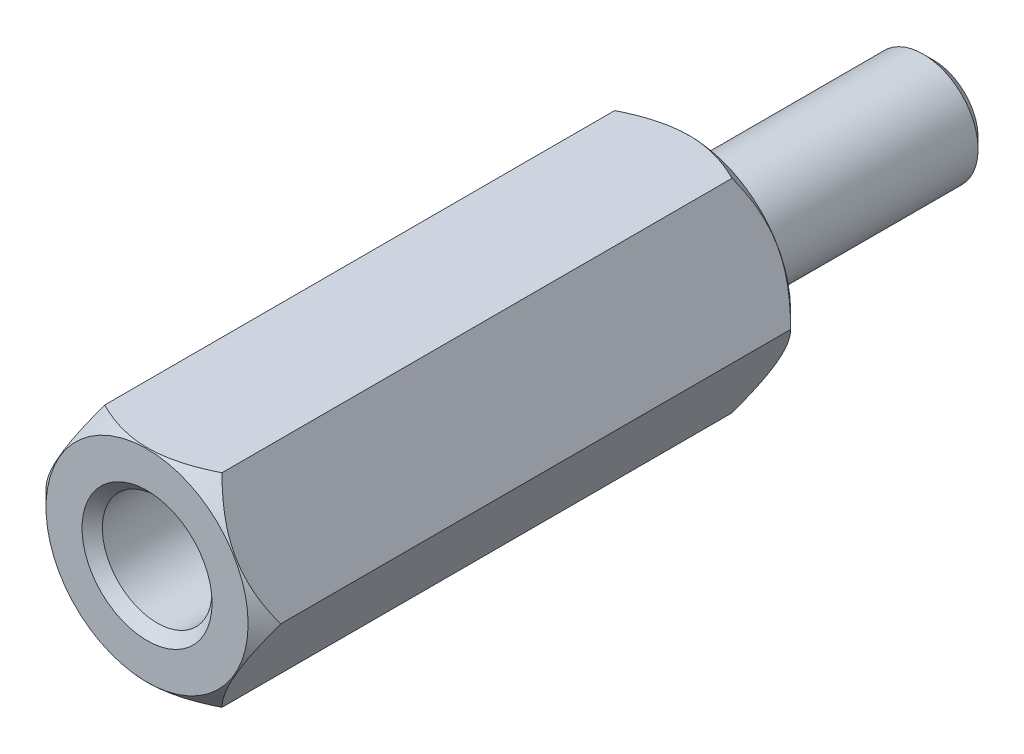
SolidWorks part; units mm, degrees
material "Brass"
ref_plane "Front Plane" through (0, 0, 0) normal (0, 0, 1) x (1, 0, 0)
ref_plane "Top Plane" through (0, 0, 0) normal (0, 1, 0) x (1, 0, 0)
ref_plane "Right Plane" through (0, 0, 0) normal (1, 0, 0) x (0, 0, -1)
ref_axis "Axis1" through (0, 0, 15.2667) along (0, 0, -1)
sketch "Sketch1" plane through (0, 0, 0) normal (0, 0, 1) x (1, 0, 0)
  line L1 (2.8868, 0) -> (1.4434, 2.5)
  line L2 (1.4434, 2.5) -> (-1.4434, 2.5)
  line L3 (-1.4434, 2.5) -> (-2.8868, 0)
  line L4 (-2.8868, 0) -> (-1.4434, -2.5)
  line L5 (-1.4434, -2.5) -> (1.4434, -2.5)
  line L6 (1.4434, -2.5) -> (2.8868, 0)
  circle A0 centre (0, 0) radius 2.5 construction
  dimension "D1" = 5
extrude "HEX" add sketch "Sketch1" along normal mid plane 13.35
hole_wizard "Tap Drill for M3x0.5 Tap1" positions "Sketch5" profile "Sketch6" hole size "M3x0.5" standard "BSI" end condition through all
sketch "Sketch5" plane through (0, 0, 6.675) normal (0, 0, 1) x (1, 0, 0)
  point P0 (0, 0)
sketch "Sketch6" plane through (0, 0, 6.675) normal (1, 0, 0) x (0, -1, 0)
  line L0 (0, 0) -> (0, 13.35)
  line L1 (0, 13.35) -> (1.35, 13.35)
  line L2 (1.35, 13.35) -> (1.35, 0)
  line L5 (1.35, 0) -> (0, 0)
  line L11 (0, -6.35) -> (0, 107.95) construction
  dimension "Thru Hole Dia." = 2.7
  dimension "Thru Hole Depth" = 13.35
sketch "Sketch7" plane through (0, 0, 0) normal (0, 1, 0) x (1, 0, 0)
  line L0 (-2.8868, 6.675) -> (-2.8868, 6.275)
  line L1 (-2.8868, -6.675) -> (-2.8868, 6.675) construction
  line L2 (-2.8868, 6.675) -> (-2.4868, 6.675)
  line L3 (-1.4434, 6.675) -> (-2.8868, 6.675) construction
  line L4 (-2.4868, 6.675) -> (-2.8868, 6.275)
  dimension "D1" = 0.4
revolve "HexChamfer" cut sketch "Sketch7" angle 360 about axis through (0, 0, 15.2667) along (0, 0, -1)
mirror "Mirror1" about plane through (0, 0, 0) normal (0, 0, 1) of "HexChamfer"
sketch "Sketch8" plane through (0, 0, -6.675) normal (0, 0, -1) x (-1, 0, 0)
  circle A0 centre (0, 0) radius 1.35
  dimension "D1" = 2.7
extrude "Thread" add sketch "Sketch8" along normal blind 6 and the other way blind 2
chamfer "InnerChamfer" distance 0.25 angle 45 3 edges at (1.35, 0, 6.675) (-1.35, 0, -12.675) (1.35, 0, -6.675)
